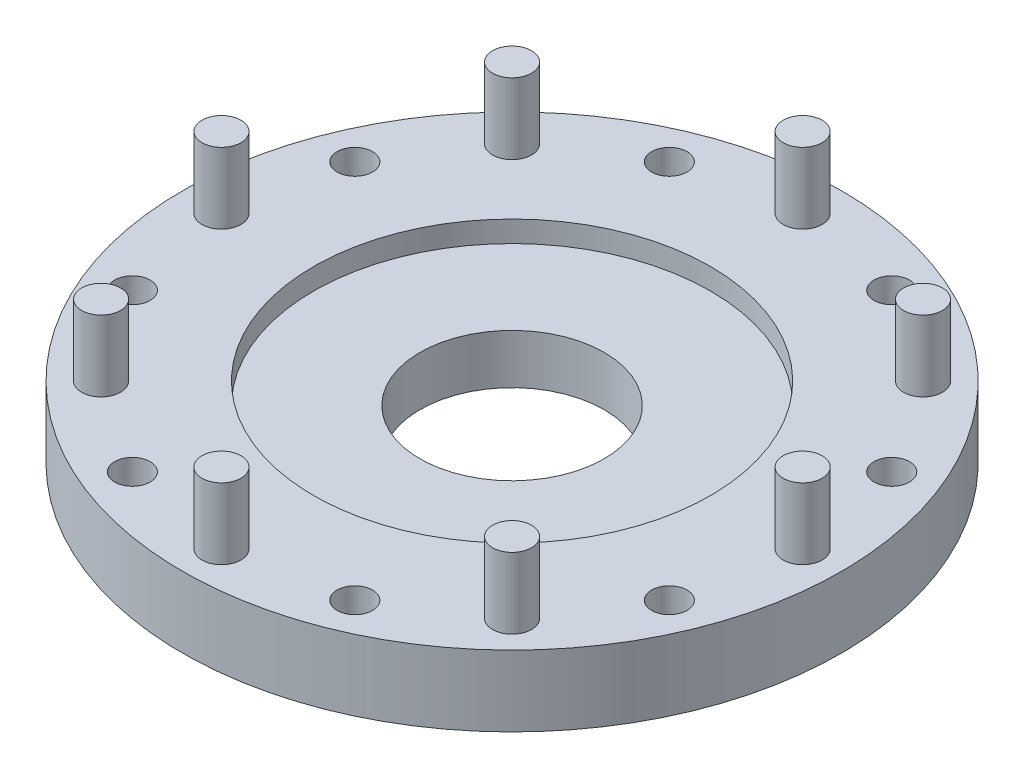
SolidWorks part; units mm, degrees
material "ABS"
ref_plane "Front Plane" through (0, 0, 0) normal (0, 0, 1) x (1, 0, 0)
ref_plane "Top Plane" through (0, 0, 0) normal (0, 1, 0) x (1, 0, 0)
ref_plane "Right Plane" through (0, 0, 0) normal (1, 0, 0) x (0, 0, -1)
sketch "Sketch1" plane through (0, 0, 0) normal (0, 0, 1) x (1, 0, 0)
  line L0 (0, -1.7519) -> (0, 48.3018) construction
  line L1 (-28, 10) -> (-46.5, 10)
  line L4 (-46.5, 10) -> (-46.5, 0)
  line L5 (-46.5, 0) -> (-13, 0)
  line L6 (-13, 0) -> (-13, 7)
  line L7 (-13, 7) -> (-28, 7)
  line L8 (-28, 7) -> (-28, 10)
  dimension "D1" = 46.5
  dimension "D3" = 3
  dimension "D2" = 28
  dimension "D4" = 13
  dimension "D5" = 10
revolve "Revolve1" add sketch "Sketch1" angle 360 about L0
sketch "Sketch2" plane through (0, 10, 0) normal (0, 1, 0) x (1, 0, 0)
  line L0 (0, 41) -> (0, 0) construction
  line L1 (0, 0) -> (15.69, 37.8791) construction
  circle A0 centre (0, 0) radius 41 construction
  circle A1 centre (0, 41) radius 2.75
  circle A2 centre (15.69, 37.8791) radius 2.5
  circle A3 centre (28.9914, 28.9914) radius 2.75
  circle A4 centre (37.8791, 15.69) radius 2.5
  circle A5 centre (41, 0) radius 2.75
  circle A6 centre (37.8791, -15.69) radius 2.5
  circle A7 centre (28.9914, -28.9914) radius 2.75
  circle A8 centre (15.69, -37.8791) radius 2.5
  circle A9 centre (0, -41) radius 2.75
  circle A10 centre (-15.69, -37.8791) radius 2.5
  circle A11 centre (-28.9914, -28.9914) radius 2.75
  circle A12 centre (-37.8791, -15.69) radius 2.5
  circle A13 centre (-41, 0) radius 2.75
  circle A14 centre (-37.8791, 15.69) radius 2.5
  circle A15 centre (-28.9914, 28.9914) radius 2.75
  circle A16 centre (-15.69, 37.8791) radius 2.5
  point P37 (0, 0)
  dimension "D1" = 82
  dimension "D2" = 5.5
  dimension "D3" = 5
  dimension "D4" = 22.5
  dimension "D5" = 8
extrude "Cut-Extrude1" cut sketch "Sketch2" against normal through all both and the other way through all
sketch "Sketch3" plane through (0, 0, 0) normal (0, 0, 1) x (1, 0, 0)
  line L0 (27.5, 4) -> (27.5, 0)
  line L2 (27.5, 0) -> (22.5, 0)
  line L3 (22.5, 0) -> (22.5, 4)
  line L6 (25, 4) -> (25, 0) construction
  line L7 (0, -19.0654) -> (0, 22.7714) construction
  line L8 (-46.5, 0) -> (46.5, 0) construction
  line L9 (27.5, 4) -> (22.5, 4)
  dimension "D1" = 25
  dimension "D2" = 4
  dimension "D3" = 5
revolve "Cut-Revolve1" cut sketch "Sketch3" angle 360 about L7
sketch "Sketch4" plane through (0, 0, 0) normal (0, -1, 0) x (1, 0, 0)
  line L0 (-19.1541, 39.8791) -> (-19.1541, 35.8791)
  line L1 (-19.1541, 35.8791) -> (-15.69, 33.8791)
  line L2 (-15.69, 33.8791) -> (-12.2259, 35.8791)
  line L3 (-12.2259, 35.8791) -> (-12.2259, 39.8791)
  line L4 (-12.2259, 39.8791) -> (-15.69, 41.8791)
  line L5 (-15.69, 41.8791) -> (-19.1541, 39.8791)
  line L6 (-15.69, 41.8791) -> (-15.69, 33.8791) construction
  line L7 (18.5184, 40.7075) -> (14.6547, 41.7428)
  line L8 (14.6547, 41.7428) -> (11.8263, 38.9143)
  line L9 (11.8263, 38.9143) -> (12.8616, 35.0506)
  line L10 (12.8616, 35.0506) -> (16.7253, 34.0154)
  line L11 (16.7253, 34.0154) -> (19.5537, 36.8438)
  line L12 (19.5537, 36.8438) -> (18.5184, 40.7075)
  line L13 (41.8791, 15.69) -> (39.8791, 19.1541)
  line L14 (39.8791, 19.1541) -> (35.8791, 19.1541)
  line L15 (35.8791, 19.1541) -> (33.8791, 15.69)
  line L16 (33.8791, 15.69) -> (35.8791, 12.2259)
  line L17 (35.8791, 12.2259) -> (39.8791, 12.2259)
  line L18 (39.8791, 12.2259) -> (41.8791, 15.69)
  line L19 (40.7075, -18.5184) -> (41.7428, -14.6547)
  line L20 (41.7428, -14.6547) -> (38.9143, -11.8263)
  line L21 (38.9143, -11.8263) -> (35.0506, -12.8616)
  line L22 (35.0506, -12.8616) -> (34.0154, -16.7253)
  line L23 (34.0154, -16.7253) -> (36.8438, -19.5537)
  line L24 (36.8438, -19.5537) -> (40.7075, -18.5184)
  line L25 (15.69, -41.8791) -> (19.1541, -39.8791)
  line L26 (19.1541, -39.8791) -> (19.1541, -35.8791)
  line L27 (19.1541, -35.8791) -> (15.69, -33.8791)
  line L28 (15.69, -33.8791) -> (12.2259, -35.8791)
  line L29 (12.2259, -35.8791) -> (12.2259, -39.8791)
  line L30 (12.2259, -39.8791) -> (15.69, -41.8791)
  line L31 (-18.5184, -40.7075) -> (-14.6547, -41.7428)
  line L32 (-14.6547, -41.7428) -> (-11.8263, -38.9143)
  line L33 (-11.8263, -38.9143) -> (-12.8616, -35.0506)
  line L34 (-12.8616, -35.0506) -> (-16.7253, -34.0154)
  line L35 (-16.7253, -34.0154) -> (-19.5537, -36.8438)
  line L36 (-19.5537, -36.8438) -> (-18.5184, -40.7075)
  line L37 (-41.8791, -15.69) -> (-39.8791, -19.1541)
  line L38 (-39.8791, -19.1541) -> (-35.8791, -19.1541)
  line L39 (-35.8791, -19.1541) -> (-33.8791, -15.69)
  line L40 (-33.8791, -15.69) -> (-35.8791, -12.2259)
  line L41 (-35.8791, -12.2259) -> (-39.8791, -12.2259)
  line L42 (-39.8791, -12.2259) -> (-41.8791, -15.69)
  line L43 (-40.7075, 18.5184) -> (-41.7428, 14.6547)
  line L44 (-41.7428, 14.6547) -> (-38.9143, 11.8263)
  line L45 (-38.9143, 11.8263) -> (-35.0506, 12.8616)
  line L46 (-35.0506, 12.8616) -> (-34.0154, 16.7253)
  line L47 (-34.0154, 16.7253) -> (-36.8438, 19.5537)
  line L48 (-36.8438, 19.5537) -> (-40.7075, 18.5184)
  line L49 (11.8263, 38.9143) -> (19.5537, 36.8438) construction
  circle A0 centre (15.69, 37.8791) radius 2.5 construction
  circle A1 centre (0, 41) radius 2.75 construction
  circle A2 centre (0, 41) radius 2.75 construction
  circle A3 centre (15.69, 37.8791) radius 2.5 construction
  circle A4 centre (-15.69, 37.8791) radius 2.5 construction
  circle A5 centre (-15.69, 37.8791) radius 2.5 construction
  point P57 (0, 0)
  dimension "D1" = 120
  dimension "D2" = 120
  dimension "D3" = 8
  dimension "D4" = 8
extrude "Cut-Extrude2" cut sketch "Sketch4" against normal blind 5
sketch "Sketch5" plane through (0, 0, 0) normal (0, -1, 0) x (1, 0, 0)
  circle A0 centre (0, 41) radius 2.75 construction
  circle A1 centre (0, 41) radius 2.75
  circle A2 centre (28.9914, 28.9914) radius 2.75 construction
  circle A3 centre (41, 0) radius 2.75 construction
  circle A4 centre (28.9914, -28.9914) radius 2.75 construction
  circle A5 centre (0, -41) radius 2.75 construction
  circle A6 centre (-28.9914, -28.9914) radius 2.75 construction
  circle A7 centre (-41, 0) radius 2.75 construction
  circle A8 centre (-28.9914, 28.9914) radius 2.75 construction
  circle A9 centre (28.9914, 28.9914) radius 2.75
  circle A10 centre (41, 0) radius 2.75
  circle A11 centre (28.9914, -28.9914) radius 2.75
  circle A12 centre (0, -41) radius 2.75
  circle A13 centre (-28.9914, -28.9914) radius 2.75
  circle A14 centre (-41, 0) radius 2.75
  circle A15 centre (-28.9914, 28.9914) radius 2.75
extrude "Boss-Extrude1" add sketch "Sketch5" against normal blind 20
equation "\"Stator_OD\"= 60'No Tolerance given"
equation "\"A\"=35.81 'taken off spec sheet for 06808 (A)"
equation "\"Rotor_ID\"= 30'No Tolerance Given"
equation "\"back_bearing_Thickness\"= 5'-0.12"
equation "\"back_bearing_OD\"= 24'-0.009 https://www.mcmaster.com/5972K155/"
equation "\"Stator_Gap\"= 0.0375'+- 0.0125 (From 1.3.3.1 Kollmorgen manual)"
equation "\"Back_mount_hole\"= 1.75'To be tapped to M2 (USE LOCKTITE)"
equation "\"facePlate_Mount_Hole\"= 2.75'To be tapped to M3"
equation "\"final_shaftD\"= 12'To fit in harmonic"
equation "\"final_shaftL\"= 5.25+3+\"sheet_thick\"+\"connector_thick\"-3+\"harmon_coupleL\"+0.5-\"shaft_Ladjust\"'length to make everything nice and aligned"
equation "\"back_bearing_ID\"= 15'"
equation "\"back_bearing_IDOD\"= 16.5'measured off CAD, actually 16.75, but rounded down to nicer number"
equation "\"rotor_shaftD\"= \"Rotor_ID\" - (\"rotor-shaft_gap\")*2'"
equation "\"front_bearing_ID\"= 12'https://www.mcmaster.com/5972K154/"
equation "\"front_bearing_OD\"= 21'-0.009"
equation "\"front_bearing_IDOD\"= 13.5'Measured off CAD. Actually 13.75, but rounded down"
equation "\"rotor-shaft_gap\" = 0.0185 '+-0.0065 (from manual)"
equation "\"front_bearing_Thickness\"= 5'-0.12"
equation "\"rotor_thickness\"= 2.4'measured off CAD"
equation "\"rotor_height\"= 32.86'+-0.075 taken off spec sheet for 06826 (C)"
equation "\"B\"= 26.3'+-0.35 taken off spec sheet for 06826"
equation "\"key_L\"= 20'-0.2 https://www.mcmaster.com/2977N19/"
equation "\"key_H\"= 4'-0.03"
equation "\"key_W\"= 4'-0.03"
equation "\"harmon_keyH\"= 13.8'+0.1 from drawing"
equation "\"harmon_coupleL\"= 21.5' taken from drawing https://www.harmonicdrive.net/_hd/content/caddownloads/dxf/csg-2uh-lw_gearheads/csg-20-100-2uh-lw.pdf"
equation "\"harmon_diam\"= 93' from drawing"
equation "\"harmon_BCD\"= 82' from drawing"
equation "\"harmon_holeD1\"= 5.5' from drawing"
equation "\"harmon_holeD2\"= 5' from drawing"
equation "\"harmon_holeAng\"= 22.5' from drawing"
equation "\"sheet_thick\"= 1/8*25.4 'random, replace w actual sheet thickness when u feel like :)"
equation "\"D1@Sketch1\"=\"harmon_diam\"/2"
equation "\"D1@Sketch2\"=\"harmon_BCD\""
equation "\"D2@Sketch2\"=\"harmon_holeD1\""
equation "\"D3@Sketch2\"=\"harmon_holeD2\""
equation "\"D4@Sketch2\"=\"harmon_holeAng\""
equation "\"nut-thickness\"= 5 'idk measure the ones in the shop and adjust"
equation "\"D1@Cut-Extrude2\"=\"nut-thickness\""
equation "\"connector_thick\"= 10' random for now"
equation "\"D5@Sketch1\"=\"connector_thick\""
equation "\"shaft_Ladjust\"= 6.5' sorry. It's silly, but it works."
equation "\"D1@Boss-Extrude1\"=\"connector_thick\"+10"
